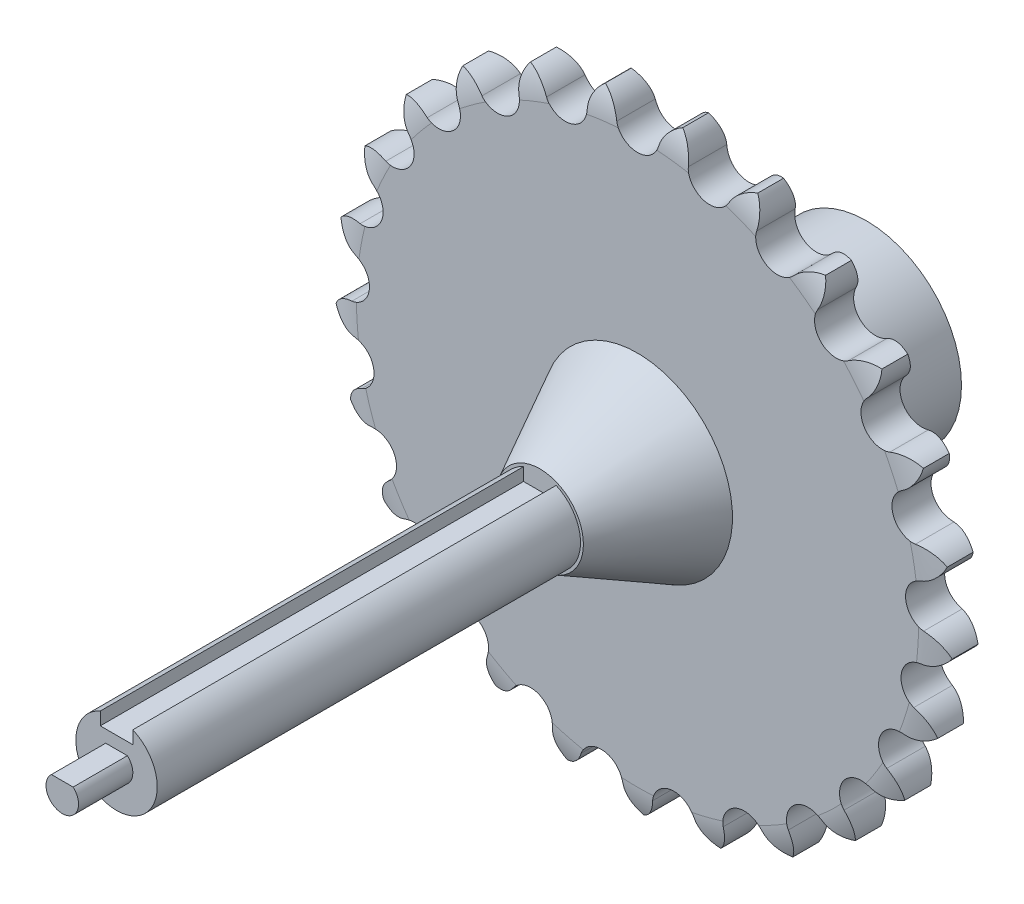
SolidWorks part; units mm, degrees
material "Acero aleado fundido"
ref_plane "Alzado" through (0, 0, 0) normal (0, 0, 1) x (1, 0, 0)
ref_plane "Planta" through (0, 0, 0) normal (0, 1, 0) x (1, 0, 0)
ref_plane "Vista lateral" through (0, 0, 0) normal (1, 0, 0) x (0, 0, -1)
sketch "Croquis1" plane through (0, 0, 0) normal (0, 0, 1) x (1, 0, 0)
  line L0 (0, 0) -> (0, 57) construction
  circle A0 centre (0, 0) radius 57 construction
  circle A1 centre (0, 0) radius 53.5 construction
  circle A2 centre (0, 0) radius 52 construction
  arc A5 (-3.8808, 52.5307) -> (3.8808, 52.5307) centre (0, 53.5) ccw
  arc A6 (7.3536, 56.5237) -> (3.8808, 52.5307) centre (9.537, 51.118) ccw
  arc A7 (15.1992, 49.7291) -> (15.3656, 51.246) centre (9.537, 51.118) ccw
  arc A8 (-7.3536, 56.5237) -> (-3.8808, 52.5307) centre (-9.537, 51.118) cw
  arc A9 (6.9343, 56.5766) -> (9.305, 51.8455) centre (3.4751, 51.8838) cw
  arc A10 (9.305, 51.8455) -> (16.8227, 49.9152) centre (13.3049, 51.8192) ccw
  arc A11 (21.1795, 52.9191) -> (16.8227, 49.9152) centre (21.9499, 47.1402) ccw
  arc A12 (20.7865, 53.0747) -> (21.9061, 47.9026) centre (16.2689, 49.3895) cw
  arc A13 (21.9061, 47.9026) -> (28.7076, 44.1634) centre (25.7738, 46.8824) ccw
  arc A14 (33.6745, 45.9894) -> (28.7076, 44.1634) centre (32.9836, 40.2005) ccw
  arc A15 (33.3325, 46.2379) -> (33.1308, 40.9498) centre (28.0405, 43.7919) cw
  arc A16 (33.1308, 40.9498) -> (38.7887, 35.6367) centre (36.6233, 38.9998) ccw
  arc A17 (44.0537, 36.1701) -> (38.7887, 35.6367) centre (41.9448, 30.7348) ccw
  arc A18 (43.7842, 36.4958) -> (42.2737, 31.424) centre (38.0501, 35.4427) cw
  arc A19 (42.2737, 31.424) -> (46.4326, 24.8707) centre (45.1715, 28.6667) ccw
  arc A20 (51.6648, 24.078) -> (46.4326, 24.8707) centre (48.2705, 19.338) ccw
  arc A21 (51.4848, 24.4605) -> (48.7604, 19.9237) centre (45.669, 24.8666) cw
  arc A22 (48.7604, 19.9237) -> (51.1589, 12.542) centre (50.8815, 16.5324) ccw
  arc A23 (56.0296, 10.4731) -> (51.1589, 12.542) centre (51.5632, 6.7261) ccw
  arc A24 (55.9504, 10.8883) -> (52.1834, 7.1716) centre (50.4183, 12.7279) cw
  arc A25 (52.1834, 7.1716) -> (52.6707, -0.5747) centre (53.3944, 3.3593) ccw
  arc A26 (56.8739, -3.79) -> (52.6707, -0.5747) centre (51.6159, -6.3085) ccw
  arc A27 (56.9004, -3.3681) -> (52.3274, -6.0312) centre (51.9996, -0.2105) cw
  arc A28 (52.3274, -6.0312) -> (50.8731, -13.6553) centre (52.5524, -10.0249) ccw
  arc A29 (54.1445, -17.8148) -> (50.8731, -13.6553) centre (48.4255, -18.9466) ccw
  arc A30 (54.2752, -17.4128) -> (49.1836, -18.855) centre (50.3136, -13.1356) cw
  arc A31 (49.1836, -18.855) -> (45.8788, -25.8779) centre (48.4082, -22.7792) ccw
  arc A32 (48.0131, -30.7204) -> (45.8788, -25.8779) centre (42.1922, -30.3943) ccw
  arc A33 (48.2396, -30.3635) -> (42.9493, -30.4941) centre (45.4662, -25.2354) cw
  arc A34 (42.9493, -30.4941) -> (38.0019, -36.4745) centre (41.2225, -34.1022) ccw
  arc A35 (38.8649, -41.6956) -> (38.0019, -36.4745) centre (33.3079, -39.9322) ccw
  arc A36 (39.173, -41.4063) -> (34.0164, -40.2172) centre (37.762, -35.7496) cw
  arc A37 (34.0164, -40.2172) -> (27.7372, -44.7793) centre (31.4465, -43.2824) ccw
  arc A38 (27.2746, -50.051) -> (27.7372, -44.7793) centre (22.3308, -46.961) ccw
  arc A39 (27.645, -49.8473) -> (22.9461, -47.4132) centre (27.6851, -44.0175) cw
  arc A40 (22.9461, -47.4132) -> (15.7296, -50.2704) centre (19.6947, -49.743) ccw
  arc A41 (13.9705, -55.2614) -> (15.7296, -50.2704) centre (9.9505, -51.0391) ccw
  arc A42 (14.3799, -55.1563) -> (10.434, -51.6301) centre (15.8686, -49.5196) cw
  arc A43 (10.434, -51.6301) -> (2.7337, -52.6029) centre (6.7053, -53.0781) ccw
  arc A44 (-0.2113, -56.9996) -> (2.7337, -52.6029) centre (-3.055, -51.9102) ccw
  arc A45 (0.2113, -56.9996) -> (-2.7337, -52.6029) centre (3.055, -51.9102) cw
  arc A46 (-2.7337, -52.6029) -> (-10.434, -51.6301) centre (-6.7053, -53.0781) ccw
  arc A47 (-14.3799, -55.1563) -> (-10.434, -51.6301) centre (-15.8686, -49.5196) ccw
  arc A48 (-13.9705, -55.2614) -> (-15.7296, -50.2704) centre (-9.9505, -51.0391) cw
  arc A49 (-15.7296, -50.2704) -> (-22.9461, -47.4132) centre (-19.6947, -49.743) ccw
  arc A50 (-27.645, -49.8473) -> (-22.9461, -47.4132) centre (-27.6851, -44.0175) ccw
  arc A51 (-27.2746, -50.051) -> (-27.7372, -44.7793) centre (-22.3308, -46.961) cw
  arc A52 (-27.7372, -44.7793) -> (-34.0164, -40.2172) centre (-31.4465, -43.2824) ccw
  arc A53 (-39.173, -41.4063) -> (-34.0164, -40.2172) centre (-37.762, -35.7496) ccw
  arc A54 (-38.8649, -41.6956) -> (-38.0019, -36.4745) centre (-33.3079, -39.9322) cw
  arc A55 (-38.0019, -36.4745) -> (-42.9493, -30.4941) centre (-41.2225, -34.1022) ccw
  arc A56 (-48.2396, -30.3635) -> (-42.9493, -30.4941) centre (-45.4662, -25.2354) ccw
  arc A57 (-48.0131, -30.7204) -> (-45.8788, -25.8779) centre (-42.1922, -30.3943) cw
  arc A58 (-45.8788, -25.8779) -> (-49.1836, -18.855) centre (-48.4082, -22.7792) ccw
  arc A59 (-54.2752, -17.4128) -> (-49.1836, -18.855) centre (-50.3136, -13.1356) ccw
  arc A60 (-54.1445, -17.8148) -> (-50.8731, -13.6553) centre (-48.4255, -18.9466) cw
  arc A61 (-50.8731, -13.6553) -> (-52.3274, -6.0312) centre (-52.5524, -10.0249) ccw
  arc A62 (-56.9004, -3.3681) -> (-52.3274, -6.0312) centre (-51.9996, -0.2105) ccw
  arc A63 (-56.8739, -3.79) -> (-52.6707, -0.5747) centre (-51.6159, -6.3085) cw
  arc A64 (-52.6707, -0.5747) -> (-52.1834, 7.1716) centre (-53.3944, 3.3593) ccw
  arc A65 (-55.9504, 10.8883) -> (-52.1834, 7.1716) centre (-50.4183, 12.7279) ccw
  arc A66 (-56.0296, 10.4731) -> (-51.1589, 12.542) centre (-51.5632, 6.7261) cw
  arc A67 (-51.1589, 12.542) -> (-48.7604, 19.9237) centre (-50.8815, 16.5324) ccw
  arc A68 (-51.4848, 24.4605) -> (-48.7604, 19.9237) centre (-45.669, 24.8666) ccw
  arc A69 (-51.6648, 24.078) -> (-46.4326, 24.8707) centre (-48.2705, 19.338) cw
  arc A70 (-46.4326, 24.8707) -> (-42.2737, 31.424) centre (-45.1715, 28.6667) ccw
  arc A71 (-43.7842, 36.4958) -> (-42.2737, 31.424) centre (-38.0501, 35.4427) ccw
  arc A72 (-44.0537, 36.1701) -> (-38.7887, 35.6367) centre (-41.9448, 30.7348) cw
  arc A73 (-38.7887, 35.6367) -> (-33.1308, 40.9498) centre (-36.6233, 38.9998) ccw
  arc A74 (-33.3325, 46.2379) -> (-33.1308, 40.9498) centre (-28.0405, 43.7919) ccw
  arc A75 (-33.6745, 45.9894) -> (-28.7076, 44.1634) centre (-32.9836, 40.2005) cw
  arc A76 (-28.7076, 44.1634) -> (-21.9061, 47.9026) centre (-25.7738, 46.8824) ccw
  arc A77 (-20.7865, 53.0747) -> (-21.9061, 47.9026) centre (-16.2689, 49.3895) ccw
  arc A78 (-21.1795, 52.9191) -> (-16.8227, 49.9152) centre (-21.9499, 47.1402) cw
  arc A79 (-16.8227, 49.9152) -> (-9.305, 51.8455) centre (-13.3049, 51.8192) ccw
  arc A80 (-6.9343, 56.5766) -> (-9.305, 51.8455) centre (-3.4751, 51.8838) ccw
  circle A81 centre (0, 0) radius 19
  point P186 (0, 0)
  dimension "D1" = 114
  dimension "D2" = 107
  dimension "D3" = 104
  dimension "D4" = 8
  dimension "D5" = 11.66
  dimension "D7" = 38
  dimension "D6" = 25
extrude "Saliente-Extruir1" add sketch "Croquis1" along normal mid plane 7.2 contours A8 A80 A79 A78 A77 A76 A75 A74 A73 A72 A71 A70 A69 A68 A67 A66 A65 A64 A63 A62 A61 A60 A59 A58 A57 A56 A55 A54 A53 A52 A51 A50 A49 A48 A47 A46 A45 A44 A43 A42 A41 A40 A39 A38 A37 A36 A35 A34 A33 A32 A31
sketch "Croquis2" plane through (0, 0, 3.6) normal (0, 0, 1) x (1, 0, 0)
  circle A0 centre (0, 0) radius 28.575
  circle A1 centre (0, 0) radius 19 construction
  circle A2 centre (0, 0) radius 19
  dimension "D1" = 57.15
extrude "Saliente-Extruir2" add sketch "Croquis2" along normal blind 19
sketch "Croquis3" plane through (0, 0, 22.6) normal (0, 0, 1) x (1, 0, 0)
  line L0 (0, 0) -> (0, 19) construction
  line L2 (-4.75, 21.4) -> (4.75, 21.4)
  line L3 (-4.75, 21.4) -> (-4.75, 16.6)
  line L4 (-4.75, 16.6) -> (4.75, 16.6)
  line L5 (4.75, 21.4) -> (4.75, 16.6)
  line L6 (-4.75, 21.4) -> (4.75, 16.6) construction
  line L7 (-4.75, 16.6) -> (4.75, 21.4) construction
  circle A1 centre (0, 0) radius 19 construction
  dimension "D1" = 9.5
  dimension "D2" = 4.8
extrude "Cortar-Extruir1" cut sketch "Croquis3" against normal through all
sketch "Croquis4" plane through (0, 0, 0) normal (1, 0, 0) x (0, 0, -1)
  line L0 (0, 56.4271) -> (0, 47.0486) construction
  line L1 (-3.6, 56.4271) -> (3.6, 56.4271) construction
  line L2 (-2.1, 58.8113) -> (-2.1, 48.3808) construction
  line L3 (-3.6, 56.4271) -> (-3.6, 51.8455) construction
  line L4 (-2.1, 57.4271) -> (-9.3502, 57.4271)
  line L5 (-9.3502, 57.4271) -> (-9.3502, 51.0771)
  line L6 (-9.3502, 51.0771) -> (-3.6, 51.0771)
  line L7 (-3.6, 52.8816) -> (-3.6, 47.9026) construction
  line L8 (9.3502, 51.0771) -> (3.6, 51.0771)
  line L9 (9.3502, 57.4271) -> (9.3502, 51.0771)
  line L10 (2.1, 57.4271) -> (9.3502, 57.4271)
  arc A0 (-2.1, 57.4271) -> (-3.6, 51.0771) centre (9.0951, 51.4305) ccw
  arc A1 (2.1, 57.4271) -> (3.6, 51.0771) centre (-9.0951, 51.4305) cw
  dimension "D2" = 12.7
  dimension "D1" = 1.5
  dimension "D3" = 1
  dimension "D4" = 6.35
ref_axis "Eje1" through (0, 0, 81.5759) along (0, 0, -1)
revolve "Cortar-Revolución1" cut sketch "Croquis4" angle 360 about axis through (0, 0, 81.5759) along (0, 0, -1)
sketch "Croquis5" plane through (0, 0, 22.6) normal (0, 0, 1) x (1, 0, 0)
  line L0 (-4.75, 18.3967) -> (-4.75, 21.4)
  line L1 (-4.75, 21.4) -> (4.75, 21.4)
  line L2 (4.75, 21.4) -> (4.75, 18.3967)
  line L3 (4.75, 18.3967) -> (4.75, 21.4) construction
  arc A0 (-4.75, 18.3967) -> (4.75, 18.3967) centre (0, 0) ccw
extrude "Saliente-Extruir4" add sketch "Croquis5" against normal blind 70.2 and the other way blind 4
sketch "Croquis6" plane through (0, 0, -47.6) normal (0, 0, -1) x (-1, 0, 0)
  line L0 (-3, 5.003) -> (-3, 7.953)
  line L1 (-3, 5.003) -> (3, 5.003)
  line L2 (3, 5.003) -> (3, 7.953)
  arc A0 (-3, 7.953) -> (3, 7.953) centre (0, 0) ccw
  circle A1 centre (0, 0) radius 10.5
  dimension "D1" = 17
  dimension "D2" = 21
  dimension "D3" = 6
  dimension "D4" = 2.95
  dimension "D5" = 2.95
extrude "Cortar-Extruir2" cut sketch "Croquis6" against normal blind 128 contours A0 L2 L1 L0
sketch "Croquis8" plane through (0, 0, -47.6) normal (0, 0, -1) x (-1, 0, 0)
  line L0 (-3, 5.003) -> (3, 5.003)
  line L1 (3, 5.003) -> (3, 7.953)
  line L2 (-3, 5.003) -> (-3, 7.953)
  line L3 (-4.75, 18.3967) -> (-4.75, 21.4)
  line L4 (-4.75, 21.4) -> (4.75, 21.4)
  line L5 (4.75, 21.4) -> (4.75, 18.3967)
  arc A0 (-3, 7.953) -> (3, 7.953) centre (0, 0) ccw
  arc A1 (-4.75, 18.3967) -> (4.75, 18.3967) centre (0, 0) ccw
extrude "Cortar-Extruir3" cut sketch "Croquis8" against normal blind 44 contours A1 L5 L4 L3
sketch "Croquis9" plane through (0, 0, 26.6) normal (0, 0, 1) x (1, 0, 0)
  circle A1 centre (0, 0) radius 28.4343
extrude "Cortar-Extruir4" cut sketch "Croquis9" against normal blind 4
sketch "Croquis10" plane through (0, 0, 22.6) normal (0, 0, 1) x (1, 0, 0)
  circle A0 centre (0, 0) radius 23.8125
  dimension "D1" = 47.625
extrude "Cortar-Extruir5" cut sketch "Croquis10" against normal blind 1
sketch "Croquis11" plane through (0, 0, -3.6) normal (0, 0, -1) x (-1, 0, 0)
  line L0 (-3, 7.953) -> (-3, 5.003) construction
  line L1 (3, 5.003) -> (-3, 5.003) construction
  line L2 (-3, 7.953) -> (-3, 5.003)
  line L3 (3, 5.003) -> (-3, 5.003)
  line L4 (3, 7.953) -> (3, 5.003) construction
  line L5 (3, 7.953) -> (3, 5.003)
  arc A0 (-3, 7.953) -> (3, 7.953) centre (0, 0) ccw construction
  arc A1 (-3, 7.953) -> (3, 7.953) centre (0, 0) ccw
extrude "Saliente-Extruir5" add sketch "Croquis11" against normal up to surface (25.2 mm away)
sketch "Croquis12" plane through (0, 0, 21.6) normal (0, 0, 1) x (1, 0, 0)
  circle A0 centre (0, 0) radius 7.5
  dimension "D1" = 15
extrude "Saliente-Extruir6" add sketch "Croquis12" along normal blind 78
sketch "Croquis13" plane through (0, 0, 99.6) normal (0, 0, 1) x (1, 0, 0)
  line L1 (-3, 4.5) -> (3, 4.5)
  line L2 (-3, 4.5) -> (-3, 10.5)
  line L3 (-3, 10.5) -> (3, 10.5)
  line L4 (3, 4.5) -> (3, 10.5)
  line L5 (-3, 4.5) -> (3, 10.5) construction
  line L6 (-3, 10.5) -> (3, 4.5) construction
  circle A0 centre (0, 0) radius 7.5 construction
  point P0 (0, 7.5)
  dimension "D1" = 6
  dimension "D2" = 6
extrude "Cortar-Extruir6" cut sketch "Croquis13" against normal up to surface (78 mm away)
sketch "Croquis14" plane through (0, 0, 99.6) normal (0, 0, 1) x (1, 0, 0)
  line L0 (2, 2.2361) -> (-2, 2.2361)
  arc A0 (-2, 2.2361) -> (2, 2.2361) centre (0, 0) ccw
  dimension "D1" = 6
  dimension "D2" = 4
extrude "Saliente-Extruir7" add sketch "Croquis14" along normal blind 10
sketch "Croquis15" plane through (0, 0, 0) normal (0, 1, 0) x (1, 0, 0)
  line L0 (7.5, -22.6) -> (17.5, -3.6)
  line L1 (-28.575, -22.6) -> (28.575, -22.6) construction
  line L2 (0, -3.6) -> (0, -31.0213) construction
  line L3 (-3.5526, -3.6) -> (3.5526, -3.6) construction
  line L4 (7.5, -99.6) -> (7.5, -21.6) construction
  line L5 (7.5, -22.6) -> (28.575, -22.6)
  line L7 (-28.575, -3.6) -> (28.575, -3.6) construction
  line L8 (28.575, -22.6) -> (28.575, -3.6)
  line L9 (28.0014, -3.6) -> (32.7752, -3.6) construction
  line L10 (28.575, -22.6) -> (28.575, -3.6) construction
  line L11 (28.575, -3.6) -> (17.5, -3.6)
  dimension "D1" = 17.5
revolve "Cortar-Revolución2" cut sketch "Croquis15" angle 360 about L2
sketch "Croquis16" plane through (0, 0, -3.6) normal (0, 0, -1) x (-1, 0, 0)
  circle A0 centre (0, 0) radius 17.5
  dimension "D1" = 35
extrude "Saliente-Extruir8" add sketch "Croquis16" along normal blind 35
